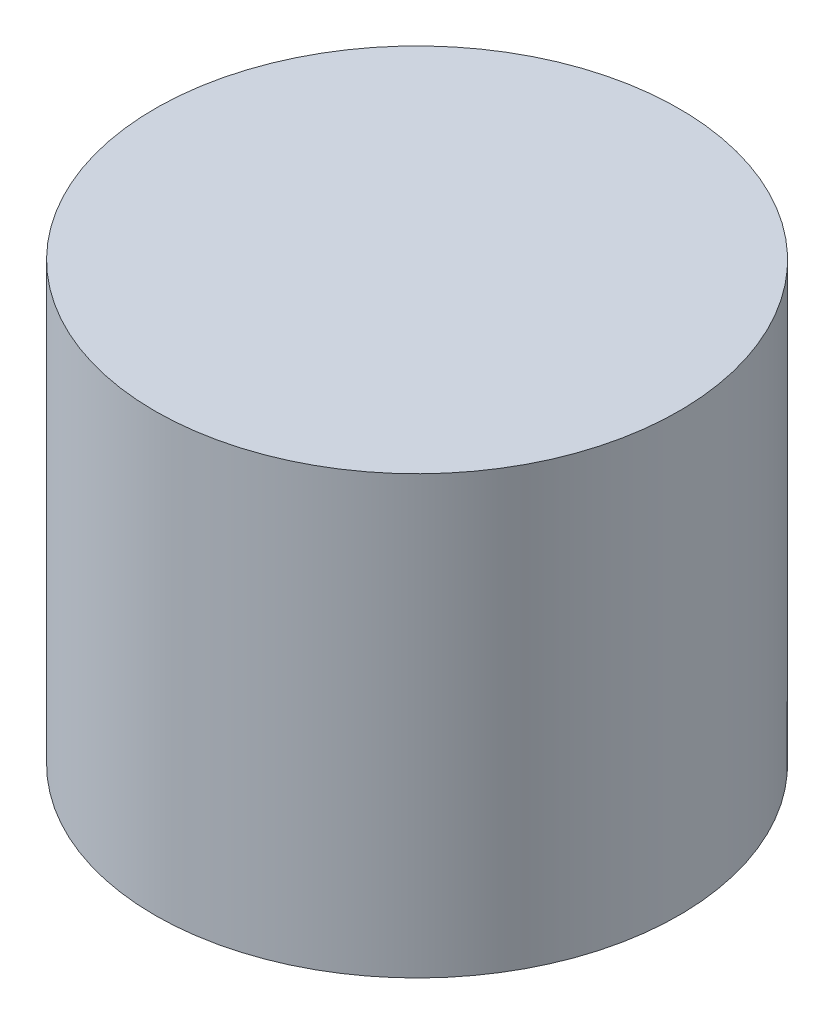
SolidWorks part; units mm, degrees
ref_plane "Front Plane" through (0, 0, 0) normal (0, 0, 1) x (1, 0, 0)
ref_plane "Top Plane" through (0, 0, 0) normal (0, 1, 0) x (1, 0, 0)
ref_plane "Right Plane" through (0, 0, 0) normal (1, 0, 0) x (0, 0, -1)
sketch "Sketch1" plane through (0, 0, 0) normal (0, 1, 0) x (1, 0, 0)
  circle A0 centre (0, 0) radius 15
  dimension "D1" = 30
extrude "Boss-Extrude1" add sketch "Sketch1" along normal blind 25
